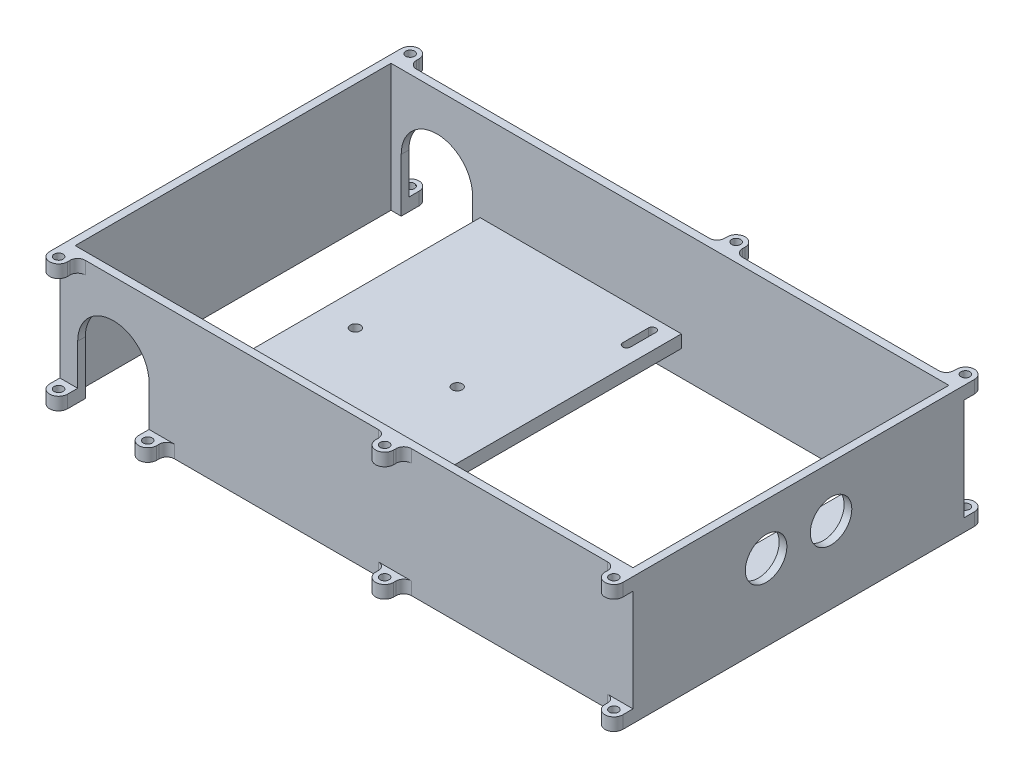
SolidWorks part; units mm, degrees
ref_plane "Front Plane" through (0, 0, 0) normal (0, 0, 1) x (1, 0, 0)
ref_plane "Top Plane" through (0, 0, 0) normal (0, 1, 0) x (1, 0, 0)
ref_plane "Right Plane" through (0, 0, 0) normal (1, 0, 0) x (0, 0, -1)
sketch "Sketch1" plane through (0, 0, 0) normal (0, 1, 0) x (1, 0, 0)
  line L0 (0, 106.6375) -> (0, -100.9097) construction
  line L1 (-202.8302, 0) -> (185.9838, 0) construction
  line L2 (-108, 62) -> (111, 62)
  line L3 (-111, 65) -> (114, 65)
  line L4 (-111, 65) -> (-111, -65)
  line L5 (-111, -65) -> (114, -65)
  line L6 (114, 65) -> (114, -65)
  line L7 (111, 62) -> (111, -62)
  line L8 (-108, -62) -> (111, -62)
  line L9 (-108, 62) -> (-108, -62)
  point P10 (-111, 0)
  dimension "D1" = 130
  dimension "D2" = 114
  dimension "D4" = 111
  dimension "D3" = 3
extrude "Boss-Extrude1" add sketch "Sketch1" along normal blind 50
sketch "Sketch3" plane through (0, 0, 65) normal (0, 0, 1) x (1, 0, 0)
  line L0 (-90, 59.9593) -> (-90, -10.4891) construction
  line L1 (-104, 0) -> (-76, 0)
  line L2 (-111, 0) -> (114, 0) construction
  line L3 (0, 61.7376) -> (0, -17.6024) construction
  line L4 (-104, 0) -> (-104, 21)
  line L5 (-76, 0) -> (-76, 21)
  arc A0 (-76, 21) -> (-104, 21) centre (-90, 21) ccw
  point P6 (-90, 0)
  dimension "D3" = 28
  dimension "D4" = 21
  dimension "D1" = 90
extrude "Cut-Extrude1" cut sketch "Sketch3" against normal through all
sketch "Sketch4" plane through (0, 0, 0) normal (0, -1, 0) x (1, 0, 0)
  line L0 (-111, 69) -> (-111, 65)
  line L1 (-104, 65) -> (-104, 69)
  line L2 (-111, 65) -> (-104, 65) construction
  line L3 (-111, 65) -> (-104, 65)
  line L5 (-76, 69) -> (-76, 65)
  line L6 (-69, 65) -> (-69, 69)
  line L7 (-76, 65) -> (-69, 65)
  line L8 (-127.3673, 0) -> (144.1525, 0) construction
  line L9 (-76, -65) -> (-69, -65)
  line L10 (-69, -65) -> (-69, -69)
  line L11 (-76, -69) -> (-76, -65)
  line L12 (-111, -65) -> (-104, -65)
  line L13 (-104, -65) -> (-104, -69)
  line L14 (-111, -69) -> (-111, -65)
  line L15 (0, 82.6192) -> (0, -78.0799) construction
  line L39 (17, -65) -> (24, -65)
  line L54 (24, -65) -> (24, -69)
  line L55 (17, -69) -> (17, -65)
  line L56 (107, -65) -> (114, -65)
  line L57 (114, -65) -> (114, -69)
  line L58 (107, -69) -> (107, -65)
  line L59 (17, 69) -> (17, 65)
  line L60 (24, 65) -> (24, 69)
  line L61 (17, 65) -> (24, 65)
  line L62 (107, 69) -> (107, 65)
  line L63 (114, 65) -> (114, 69)
  line L64 (107, 65) -> (114, 65)
  arc A0 (-104, 69) -> (-111, 69) centre (-107.5, 69) ccw
  circle A1 centre (-107.5, 69) radius 1.75
  arc A2 (-69, 69) -> (-76, 69) centre (-72.5, 69) ccw
  circle A3 centre (-72.5, 69) radius 1.75
  circle A4 centre (-72.5, -69) radius 1.75
  arc A5 (-69, -69) -> (-76, -69) centre (-72.5, -69) cw
  circle A6 centre (-107.5, -69) radius 1.75
  arc A7 (-104, -69) -> (-111, -69) centre (-107.5, -69) cw
  circle A34 centre (20.5, -69) radius 1.75
  arc A35 (24, -69) -> (17, -69) centre (20.5, -69) cw
  circle A36 centre (110.5, -69) radius 1.75
  arc A37 (114, -69) -> (107, -69) centre (110.5, -69) cw
  arc A38 (24, 69) -> (17, 69) centre (20.5, 69) ccw
  circle A39 centre (20.5, 69) radius 1.75
  arc A40 (114, 69) -> (107, 69) centre (110.5, 69) ccw
  circle A41 centre (110.5, 69) radius 1.75
  dimension "D1" = 7
  dimension "D3" = 3.5
  dimension "D8" = 2
  dimension "D9" = 183
  dimension "D11" = 2
  dimension "D12" = 90
  dimension "D13" = 183
  dimension "D7" = 90
  dimension "D2" = 4
  dimension "D4" = 2
  dimension "D5" = 28
  dimension "D6" = 2
  dimension "D10" = 2
extrude "Boss-Extrude2" add sketch "Sketch4" against normal blind 5
sketch "Sketch6" plane through (114, 0, 0) normal (1, 0, 0) x (0, 0, -1)
  line L0 (0, 61.3823) -> (0, -13.3348) construction
  line L1 (-64.15, 30) -> (65.85, 30) construction
  line L4 (-69, 0) -> (69, 0) construction
  line L5 (-20.5, 38.5) -> (20.5, 38.5) construction
  line L6 (-20.5, 38.5) -> (-20.5, 21.5) construction
  line L7 (-20.5, 21.5) -> (20.5, 21.5) construction
  line L8 (20.5, 38.5) -> (20.5, 21.5) construction
  circle A0 centre (-12.75, 30) radius 8.15
  circle A1 centre (12.75, 30) radius 8.15
  point P17 (0, 38.5)
  point P18 (-20.5, 30)
  dimension "D1" = 16.3
  dimension "D2" = 16.3
  dimension "D3" = 25.5
  dimension "D4" = 12.75
  dimension "D5" = 41
  dimension "D6" = 17
  dimension "D11" = 30
extrude "Cut-Extrude2" cut sketch "Sketch6" against normal blind 10
sketch "Sketch8" plane through (0, 50, 0) normal (0, 1, 0) x (1, 0, 0)
  line L0 (114, 65) -> (107, 65) construction
  line L1 (114, -65) -> (114, -69) construction
  line L2 (107, -69) -> (107, -65) construction
  line L3 (107, -65) -> (114, -65) construction
  line L4 (-104, 65) -> (-111, 65) construction
  line L5 (24, 65) -> (17, 65) construction
  line L6 (24, -65) -> (24, -69) construction
  line L7 (17, -69) -> (17, -65) construction
  line L8 (17, -65) -> (24, -65) construction
  line L9 (-111, -65) -> (-104, -65) construction
  line L10 (-104, -65) -> (-104, -69) construction
  line L11 (-111, -69) -> (-111, -65) construction
  line L12 (17, 65) -> (17, 69) construction
  line L13 (24, 69) -> (24, 65) construction
  line L14 (107, 65) -> (107, 69) construction
  line L15 (114, 69) -> (114, 65) construction
  line L16 (-104, 69) -> (-104, 65) construction
  line L17 (-111, 65) -> (-111, 69) construction
  line L18 (114, 65) -> (107, 65)
  line L19 (114, -65) -> (114, -69)
  line L20 (107, -69) -> (107, -65)
  line L21 (107, -65) -> (114, -65)
  line L22 (-104, 65) -> (-111, 65)
  line L23 (24, 65) -> (17, 65)
  line L24 (24, -65) -> (24, -69)
  line L25 (17, -69) -> (17, -65)
  line L26 (17, -65) -> (24, -65)
  line L27 (-111, -65) -> (-104, -65)
  line L28 (-104, -65) -> (-104, -69)
  line L29 (-111, -69) -> (-111, -65)
  line L30 (17, 65) -> (17, 69)
  line L31 (24, 69) -> (24, 65)
  line L32 (107, 65) -> (107, 69)
  line L33 (114, 69) -> (114, 65)
  line L34 (-104, 69) -> (-104, 65)
  line L35 (-111, 65) -> (-111, 69)
  circle A0 centre (110.5, -69) radius 1.75 construction
  arc A1 (107, -69) -> (114, -69) centre (110.5, -69) ccw construction
  arc A2 (17, -69) -> (24, -69) centre (20.5, -69) ccw construction
  arc A3 (-111, -69) -> (-104, -69) centre (-107.5, -69) ccw construction
  circle A4 centre (20.5, 69) radius 1.75 construction
  arc A5 (24, 69) -> (17, 69) centre (20.5, 69) ccw construction
  circle A6 centre (110.5, 69) radius 1.75 construction
  arc A7 (114, 69) -> (107, 69) centre (110.5, 69) ccw construction
  circle A8 centre (-107.5, 69) radius 1.75 construction
  arc A9 (-104, 69) -> (-111, 69) centre (-107.5, 69) ccw construction
  circle A10 centre (110.5, -69) radius 1.75
  arc A11 (107, -69) -> (114, -69) centre (110.5, -69) ccw
  arc A12 (17, -69) -> (24, -69) centre (20.5, -69) ccw
  arc A13 (-111, -69) -> (-104, -69) centre (-107.5, -69) ccw
  circle A14 centre (20.5, 69) radius 1.75
  arc A15 (24, 69) -> (17, 69) centre (20.5, 69) ccw
  circle A16 centre (110.5, 69) radius 1.75
  arc A17 (114, 69) -> (107, 69) centre (110.5, 69) ccw
  circle A18 centre (-107.5, 69) radius 1.75
  arc A19 (-104, 69) -> (-111, 69) centre (-107.5, 69) ccw
  circle A20 centre (20.5, -69) radius 1.75 construction
  circle A21 centre (-107.5, -69) radius 1.75 construction
  circle A22 centre (20.5, -69) radius 1.75
  circle A23 centre (-107.5, -69) radius 1.75
extrude "Boss-Extrude5" add sketch "Sketch8" against normal blind 5
sketch "Sketch9" plane through (0, 0, 0) normal (0, -1, 0) x (1, 0, 0)
  line L0 (-144.1136, 0) -> (149.2488, 0) construction
  line L1 (99, 62) -> (99, -62) construction
  line L2 (-76, 62) -> (111, 62) construction
  line L3 (111, -62) -> (-76, -62) construction
  line L4 (-1, 62) -> (-1, -62) construction
  line L7 (111, 62) -> (111, -62) construction
  line L11 (92, 62) -> (92, -62)
  line L15 (-8, -62) -> (6, -62)
  line L17 (92, -62) -> (111, -62)
  line L25 (92, 62) -> (111, 62)
  line L26 (97.5, 57.5) -> (97.5, 47.5)
  line L28 (100.5, 57.5) -> (100.5, 47.5)
  line L29 (-2.5, 57.5) -> (-2.5, 47.5)
  line L30 (0.5, 57.5) -> (0.5, 47.5)
  line L32 (-8, 62) -> (-8, -62)
  line L33 (6, 62) -> (6, -62)
  line L41 (-2.5, 62) -> (-2.5, -62) construction
  line L42 (0.5, 62) -> (0.5, -62) construction
  line L43 (100.5, 62) -> (100.5, -62) construction
  line L44 (97.5, 62) -> (97.5, -62) construction
  line L45 (-8, 62) -> (6, 62)
  line L46 (111, 62) -> (111, -62)
  line L47 (-2.5, -47.5) -> (-2.5, -57.5)
  line L48 (0.5, -47.5) -> (0.5, -57.5)
  line L49 (100.5, -47.5) -> (100.5, -57.5)
  line L50 (97.5, -47.5) -> (97.5, -57.5)
  arc A9 (0.5, 57.5) -> (-2.5, 57.5) centre (-1, 57.5) ccw
  arc A10 (100.5, 57.5) -> (97.5, 57.5) centre (99, 57.5) ccw
  arc A11 (-2.5, -57.5) -> (0.5, -57.5) centre (-1, -57.5) ccw
  arc A12 (97.5, -57.5) -> (100.5, -57.5) centre (99, -57.5) ccw
  arc A13 (-2.5, 47.5) -> (0.5, 47.5) centre (-1, 47.5) ccw
  arc A14 (97.5, 47.5) -> (100.5, 47.5) centre (99, 47.5) ccw
  arc A15 (0.5, -47.5) -> (-2.5, -47.5) centre (-1, -47.5) ccw
  arc A16 (100.5, -47.5) -> (97.5, -47.5) centre (99, -47.5) ccw
  dimension "D12" = 57.5
  dimension "D13" = 115
  dimension "D14" = 57.5
  dimension "D15" = 10
  dimension "D11" = 115
  dimension "D3" = 10
  dimension "D16" = 10
  dimension "D17" = 10
  dimension "D7" = 1.5
  dimension "D1" = 100
  dimension "D2" = 12
  dimension "D4" = 7
  dimension "D5" = 1.5
  dimension "D6" = 1.5
  dimension "D8" = 1.5
  dimension "D9" = 7
  dimension "D10" = 7
extrude "Boss-Extrude6" add sketch "Sketch9" against normal blind 5 from offset 10 offset against normal yes
fillet "Fillet1" radius 3 16 edges at (107, 2.5, -65) (107, 47.5, -65) (17, 47.5, -65) (-69, 2.5, -65) (17, 2.5, -65) (24, 2.5, -65) (24, 47.5, -65) (-104, 47.5, -65) (107, 2.5, 65) (107, 47.5, 65) (24, 47.5, 65) (17, 47.5, 65) (17, 2.5, 65) (24, 2.5, 65) (-104, 47.5, 65) (-69, 2.5, 65)
sketch "Sketch10" plane through (-8, 0, 0) normal (-1, 0, 0) x (0, 0, 1)
  line L4 (-62, 10) -> (62, 10)
  line L5 (62, 10) -> (62, 15)
  line L6 (62, 15) -> (-62, 15)
  line L7 (-62, 15) -> (-62, 10)
  line L8 (-62, 10) -> (62, 10)
  line L9 (62, 10) -> (62, 15)
  line L10 (62, 15) -> (-62, 15)
  line L11 (-62, 15) -> (-62, 10)
  dimension "D1" = 0
extrude "Boss-Extrude7" add sketch "Sketch10" along normal blind 65
sketch "Sketch11" plane through (0, 15, 0) normal (0, 1, 0) x (1, 0, 0)
  line L0 (-40, 62) -> (-40, -62) construction
  line L1 (111, 62) -> (-108, 62) construction
  line L2 (-108, -62) -> (111, -62) construction
  line L3 (-73, -62) -> (-73, 62) construction
  line L4 (-62, 0) -> (-18, 0) construction
  line L6 (-73, 62) -> (6, 62) construction
  circle A0 centre (-60, 0) radius 2
  circle A1 centre (-20, 0) radius 2
  dimension "D2" = 4
  dimension "D3" = 4
  dimension "D4" = 20
  dimension "D5" = 20
  dimension "D1" = 33
  dimension "D6" = 62
extrude "Cut-Extrude3" cut sketch "Sketch11" against normal through all
